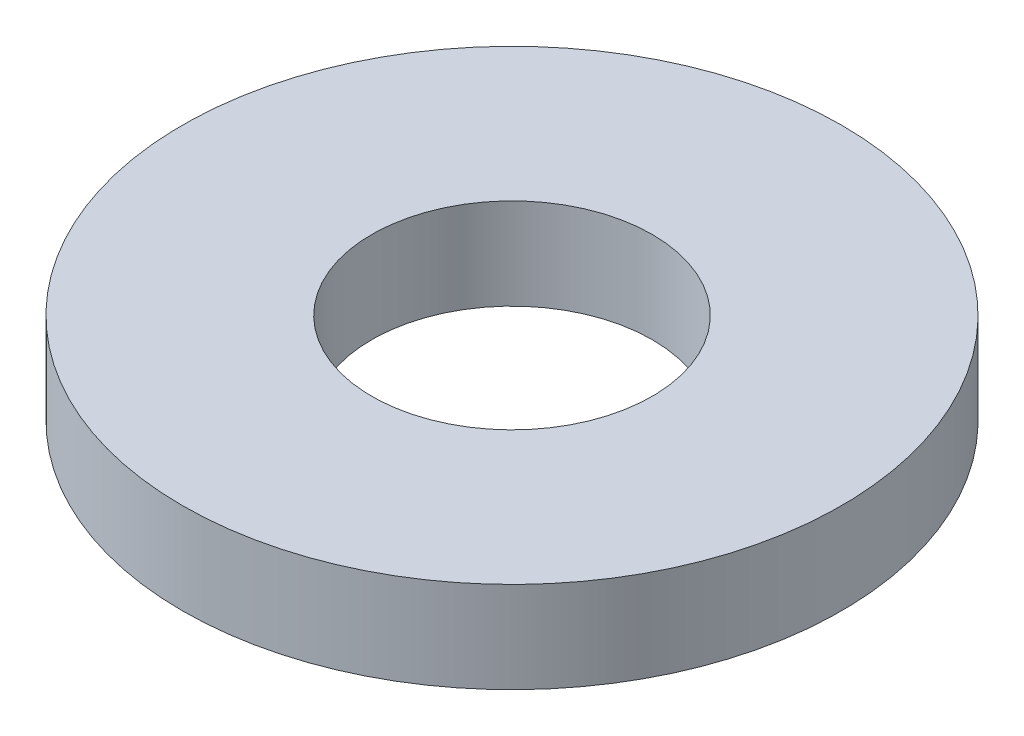
SolidWorks part; units mm, degrees
ref_plane "前视基准面" through (0, 0, 0) normal (0, 0, 1) x (1, 0, 0)
ref_plane "上视基准面" through (0, 0, 0) normal (0, 1, 0) x (1, 0, 0)
ref_plane "右视基准面" through (0, 0, 0) normal (1, 0, 0) x (0, 0, -1)
sketch "草图1" plane through (0, 0, 0) normal (0, 1, 0) x (1, 0, 0)
  circle A0 centre (0, 0) radius 23.5
  circle A1 centre (0, 0) radius 10
extrude "凸台-拉伸1" add sketch "草图1" along normal blind 6.5
